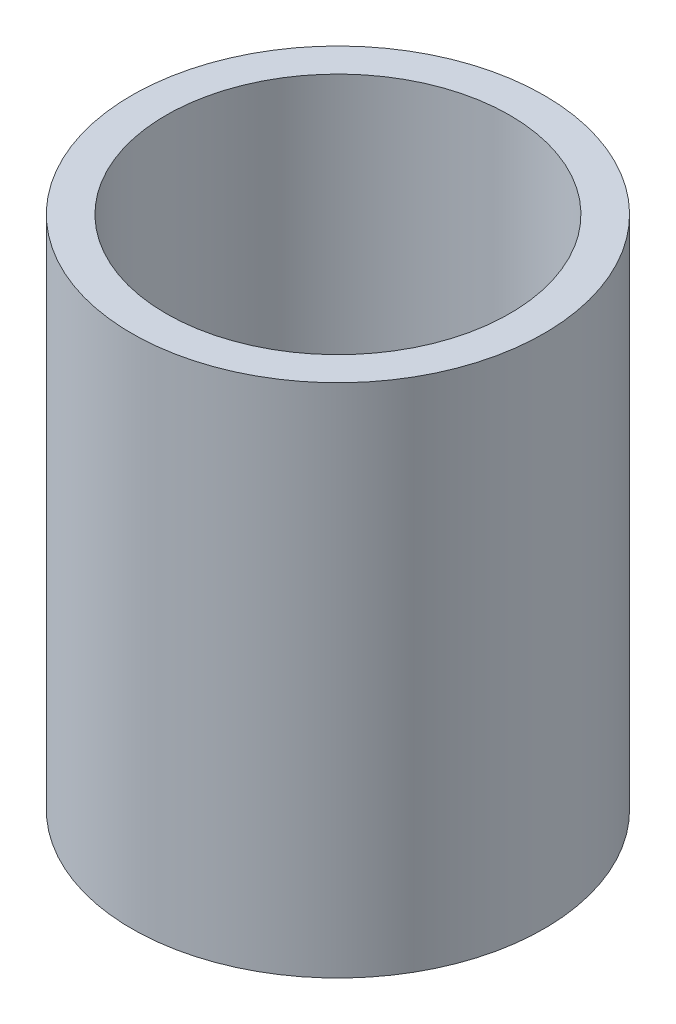
SolidWorks part; units mm, degrees
ref_plane "Front Plane" through (0, 0, 0) normal (0, 0, 1) x (1, 0, 0)
ref_plane "Top Plane" through (0, 0, 0) normal (0, 1, 0) x (1, 0, 0)
ref_plane "Right Plane" through (0, 0, 0) normal (1, 0, 0) x (0, 0, -1)
sketch "Sketch1" plane through (0, 0, 0) normal (0, 1, 0) x (1, 0, 0)
  circle A0 centre (0, 0.545) radius 15
  circle A1 centre (0, 0.545) radius 18
  dimension "D1" = 30
  dimension "D2" = 36
extrude "Boss-Extrude1" add sketch "Sketch1" along normal blind 45
